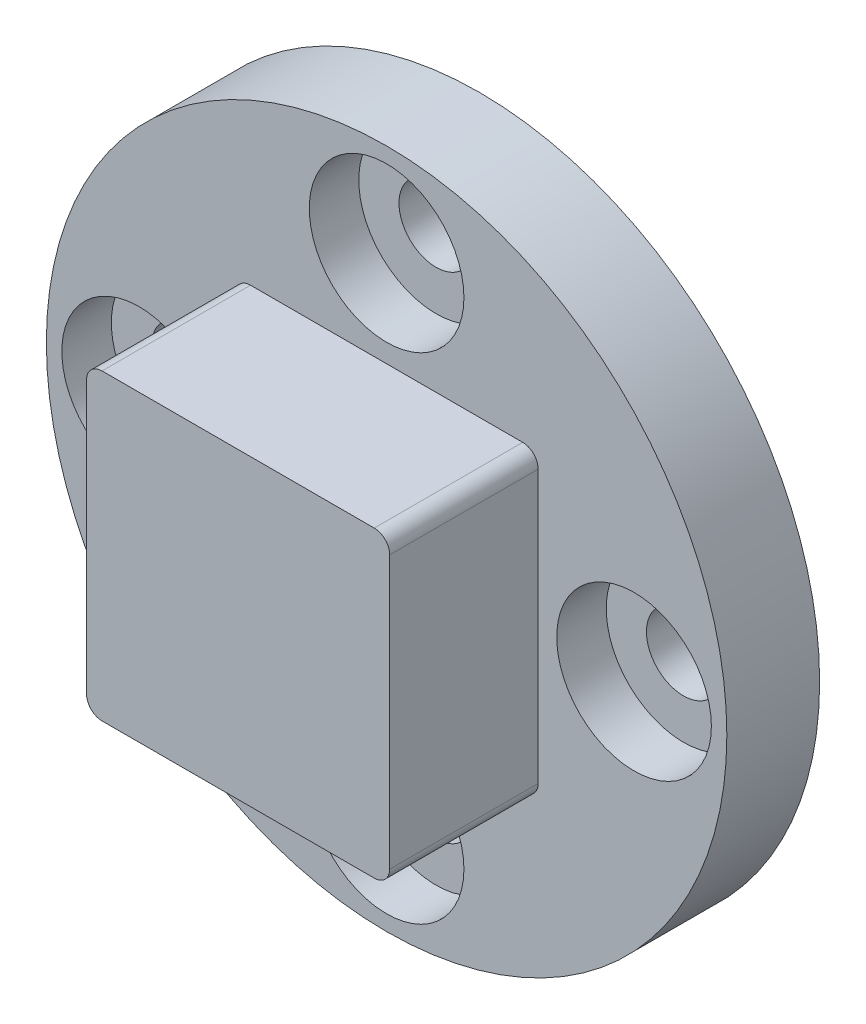
SolidWorks part; units mm, degrees
ref_plane "Płaszczyzna przednia" through (0, 0, 0) normal (0, 0, 1) x (1, 0, 0)
ref_plane "Płaszczyzna górna" through (0, 0, 0) normal (0, 1, 0) x (1, 0, 0)
ref_plane "Płaszczyzna prawa" through (0, 0, 0) normal (1, 0, 0) x (0, 0, -1)
sketch "Szkic1" plane through (0, 0, 0) normal (0, 0, 1) x (1, 0, 0)
  circle A0 centre (0, 0) radius 11
  dimension "D1" = 22
extrude "Dodanie-wyciągnięcie1" add sketch "Szkic1" along normal blind 3
sketch "Szkic2" plane through (0, 0, 3) normal (0, 0, 1) x (1, 0, 0)
  line L0 (0, 0) -> (0, 8) construction
  line L1 (0, 0) -> (-8, 0) construction
  line L2 (0, 0) -> (0, -8) construction
  line L3 (0, 0) -> (8, 0) construction
  circle A0 centre (0, 0) radius 8
  point P3 (0, 8)
  point P5 (-8, 0)
  point P6 (0, -8)
  point P7 (8, 0)
  point P10 (0, 8)
  point P16 (8, 0)
  point P18 (0, -8)
  point P22 (-8, 0)
  dimension "D1" = 16
hole_wizard "Pogłębienie walcowe pod M2 Śrubę z łbem stożkowym ściętym1" positions "Szkic2" profile "Szkic3" counterbore size "M2" standard "DIN" end condition through all
sketch "Szkic3" plane through (-8, 0, 3) normal (1, 0, 0) x (0, -1, 0)
  line L0 (0, 0) -> (0, 3)
  line L1 (0, 3) -> (1.2, 3)
  line L3 (1.2, 3) -> (1.2, 1.6)
  line L4 (1.2, 1.6) -> (2.5, 1.6)
  line L5 (2.5, 1.6) -> (2.5, 0)
  line L7 (2.5, 0) -> (0, 0)
  line L11 (0, -6.35) -> (0, 107.95) construction
  dimension "Średnica otworu na wylot" = 2.4
  dimension "Głębokość otworu na wylot" = 3
  dimension "Średnica pogłębienia walcowego" = 5
  dimension "Głębokość pogłębienia walcowego" = 1.6
sketch "Szkic4" plane through (0, 0, 3) normal (0, 0, 1) x (1, 0, 0)
  line L1 (-4.9, 4.9) -> (4.9, 4.9)
  line L2 (-4.9, 4.9) -> (-4.9, -4.9)
  line L3 (-4.9, -4.9) -> (4.9, -4.9)
  line L4 (4.9, 4.9) -> (4.9, -4.9)
  line L5 (-4.9, 4.9) -> (4.9, -4.9) construction
  line L6 (-4.9, -4.9) -> (4.9, 4.9) construction
  point P0 (0, 0)
  dimension "D1" = 9.8
extrude "Dodanie-wyciągnięcie2" add sketch "Szkic4" along normal blind 4.8
fillet "Zaokrąglenie1" radius 0.5 4 edges at (-4.9, 4.9, 5.4) (4.9, 4.9, 5.4) (4.9, -4.9, 5.4) (-4.9, -4.9, 5.4)
